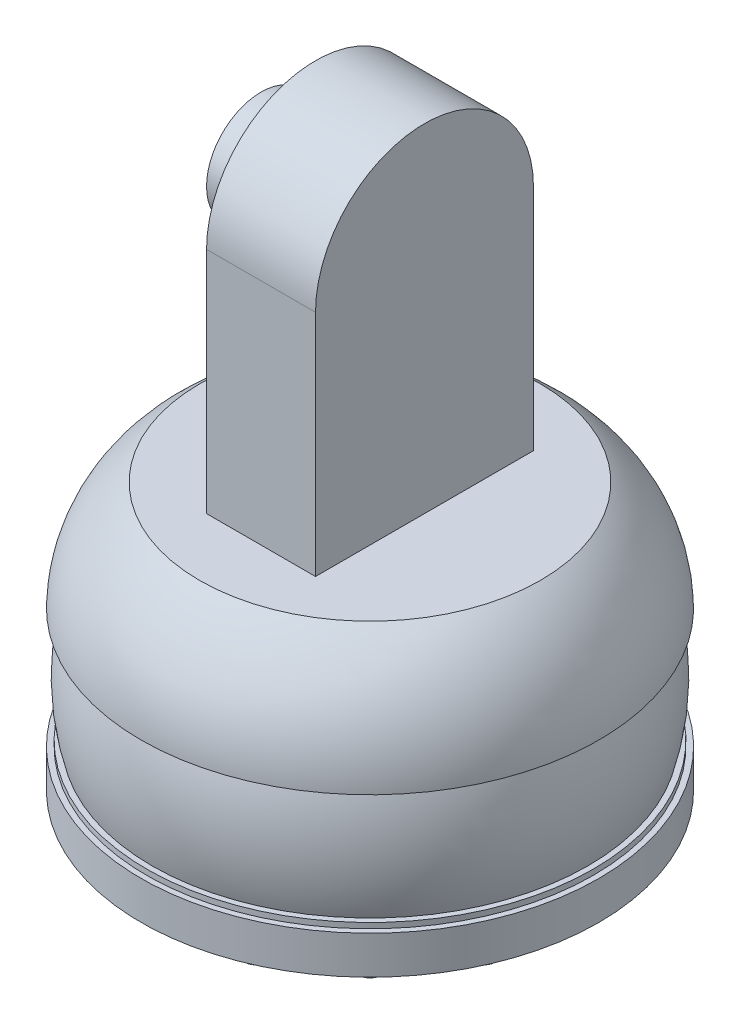
SolidWorks part; units mm, degrees
ref_plane "Front Plane" through (0, 0, 0) normal (0, 0, 1) x (1, 0, 0)
ref_plane "Top Plane" through (0, 0, 0) normal (0, 1, 0) x (1, 0, 0)
ref_plane "Right Plane" through (0, 0, 0) normal (1, 0, 0) x (0, 0, -1)
sketch "Sketch1" plane through (0, 0, 0) normal (1, 0, 0) x (0, 0, -1)
  line L0 (0, 0) -> (-42, 0)
  line L1 (0, 0) -> (0, 20)
  line L3 (0, 20) -> (-31.2632, 20)
  arc A1 (-42, 0) -> (-31.2632, 20) centre (-17.0057, -0.536) cw
  dimension "D3" = 25
  dimension "D1" = 42
  dimension "D2" = 20
revolve "Revolve1" add sketch "Sketch1" angle 360 about L1
sketch "Sketch2" plane through (0, 0, 0) normal (0, -1, 0) x (1, 0, 0)
  circle A0 centre (0, 0) radius 39.5
  dimension "D1" = 79
extrude "Boss-Extrude1" add sketch "Sketch2" along normal blind 1
sketch "Sketch3" plane through (0, 0, 0) normal (0, 0, 1) x (1, 0, 0)
  line L0 (0, -1) -> (0, -21)
  line L1 (-39.5, -1) -> (39.5, -1) construction
  line L2 (0, -1) -> (-40, -1)
  line L3 (0, -21) -> (-40, -21)
  arc A0 (-40, -1) -> (-40, -21) centre (-4.377, -11) ccw
  dimension "D3" = 37
  dimension "D1" = 40
  dimension "D2" = 20
revolve "Revolve2" add sketch "Sketch3" angle 360 about L0
sketch "Sketch4" plane through (0, -21, 0) normal (0, -1, 0) x (1, 0, 0)
  circle A0 centre (0, 0) radius 41
  dimension "D1" = 82
extrude "Boss-Extrude2" add sketch "Sketch4" along normal blind 1
sketch "Sketch5" plane through (0, -22, 0) normal (0, -1, 0) x (1, 0, 0)
  circle A0 centre (0, 0) radius 42
  dimension "D1" = 84
extrude "Boss-Extrude3" add sketch "Sketch5" along normal blind 7
sketch "Sketch6" plane through (0, -29, 0) normal (0, -1, 0) x (1, 0, 0)
  circle A0 centre (0, 0) radius 35
  dimension "D1" = 70
extrude "Boss-Extrude4" add sketch "Sketch6" along normal blind 3
sketch "Sketch7" plane through (0, -29, 0) normal (0, -1, 0) x (1, 0, 0)
  line L0 (35, 0) -> (42, 0)
  circle A0 centre (0, 0) radius 35 construction
  circle A1 centre (0, 0) radius 42 construction
  circle A2 centre (38.5, 0) radius 2.25
  circle A3 centre (38.5, 0) radius 1.5
  point P3 (35, 0)
  point P4 (42, 0)
  dimension "D2" = 3
  dimension "D3" = 4.5
extrude "Boss-Extrude5" add sketch "Sketch7" along normal blind 1 contours A3 L0 A2 | A3 L0 A2
pattern_circular "CirPattern1" count 16 over 360 about axis through (0, 0, 0) along (0, 1, 0) of "Boss-Extrude5"
sketch "Sketch8" plane through (0, 20, 0) normal (0, 1, 0) x (1, 0, 0)
  line L1 (-10, -20) -> (10, -20)
  line L2 (-10, -20) -> (-10, 20)
  line L3 (-10, 20) -> (10, 20)
  line L4 (10, -20) -> (10, 20)
  line L5 (-10, -20) -> (10, 20) construction
  line L6 (-10, 20) -> (10, -20) construction
  point P0 (0, 0)
  dimension "D1" = 40
  dimension "D2" = 20
extrude "Boss-Extrude6" add sketch "Sketch8" along normal blind 42
sketch "Sketch9" plane through (10, 0, 0) normal (1, 0, 0) x (0, 0, -1)
  line L0 (-20, 62) -> (20, 62) construction
  circle A0 centre (0, 62) radius 20
extrude "Boss-Extrude7" add sketch "Sketch9" against normal up to surface (20 mm away) up to face at (-10, 41, 0)
sketch "Sketch10" plane through (-10, 0, 0) normal (-1, 0, 0) x (0, 0, 1)
  circle A0 centre (0, 62) radius 10
  dimension "D1" = 20
extrude "Boss-Extrude8" add sketch "Sketch10" along normal blind 10
sketch "Sketch11" plane through (0, -32, 0) normal (0, -1, 0) x (1, 0, 0)
  circle A0 centre (0, 0) radius 10
  dimension "D1" = 20
extrude "Boss-Extrude9" add sketch "Sketch11" along normal blind 10
